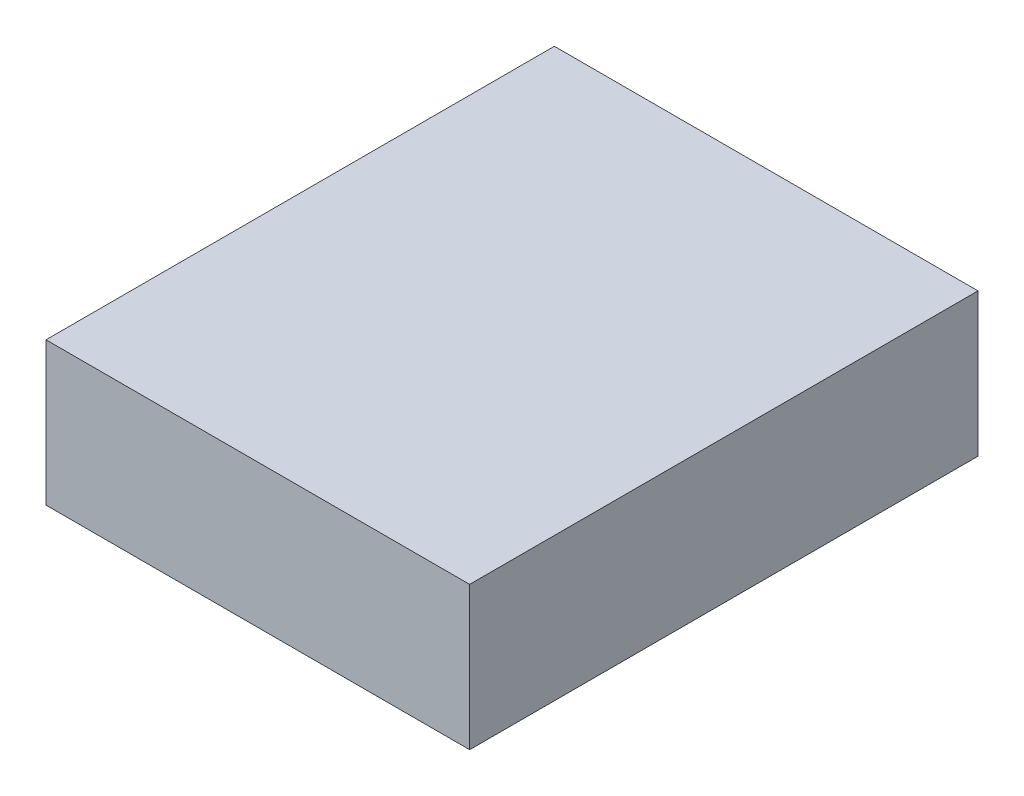
SolidWorks part; units mm, degrees
material "Rubber"
ref_plane "Front Plane" through (0, 0, 0) normal (0, 0, 1) x (1, 0, 0)
ref_plane "Top Plane" through (0, 0, 0) normal (0, 1, 0) x (1, 0, 0)
ref_plane "Right Plane" through (0, 0, 0) normal (1, 0, 0) x (0, 0, -1)
sketch "Sketch1" plane through (0, 0, 0) normal (0, 0, 1) x (1, 0, 0)
  line L1 (-25, -8.45) -> (25, -8.45)
  line L2 (-25, -8.45) -> (-25, 8.45)
  line L3 (-25, 8.45) -> (25, 8.45)
  line L4 (25, -8.45) -> (25, 8.45)
  line L5 (-25, -8.45) -> (25, 8.45) construction
  line L6 (-25, 8.45) -> (25, -8.45) construction
  point P0 (0, 0)
  dimension "D1" = 16.9
  dimension "D2" = 50
extrude "Boss-Extrude1" add sketch "Sketch1" along normal blind 60
